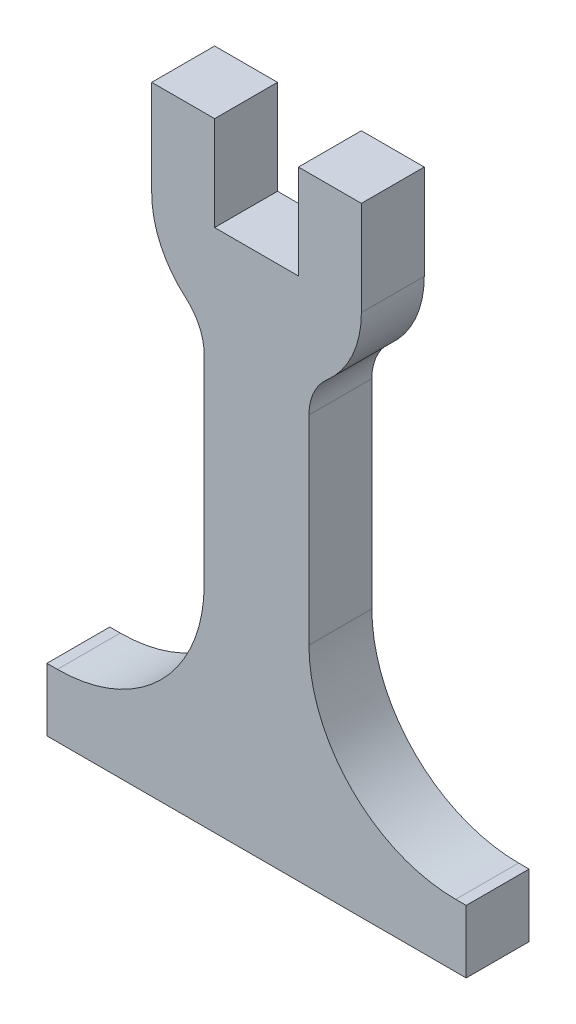
SolidWorks part; units mm, degrees
material "Pinho"
ref_plane "Plano frontal" through (0, 0, 0) normal (0, 0, 1) x (1, 0, 0)
ref_plane "Plano superior" through (0, 0, 0) normal (0, 1, 0) x (1, 0, 0)
ref_plane "Plano direito" through (0, 0, 0) normal (1, 0, 0) x (0, 0, -1)
sketch "Esboço1" plane through (0, 0, 0) normal (0, 0, 1) x (1, 0, 0)
  line L0 (3, 0) -> (7, 0)
  line L2 (0, 0) -> (0, 3)
  line L4 (3, 0) -> (3, 3)
  line L5 (2.5, -6.25) -> (2.5, -5.4903)
  line L7 (7, 0) -> (7, 3)
  line L9 (10, 0) -> (10, 3)
  line L10 (0, -25) -> (10, -25)
  line L11 (7.5, -5.4903) -> (7.5, -6.25)
  line L12 (-5, -25) -> (15, -25)
  line L13 (0, 0) -> (0, -0.0759)
  line L14 (3, 3) -> (3, 4.5)
  line L15 (2.5, -12.5) -> (2.5, -6.25)
  line L16 (7.5, -12.5) -> (7.5, -6.25)
  line L17 (10, 0) -> (10, -0.0154)
  line L18 (10, -3) -> (9.9903, -3)
  line L19 (2.5, -12.5) -> (2.5, -15)
  line L20 (0, -3) -> (0.0097, -3)
  line L21 (-5, -25) -> (-5, -22)
  line L22 (15, -25) -> (15, -22)
  line L23 (7, 4.5) -> (10, 4.5)
  line L24 (10, 4.5) -> (10, 3)
  line L25 (-5, -22) -> (-4.5, -22)
  line L26 (7, 3) -> (7, 4.5)
  line L27 (14.5, -22) -> (15, -22)
  line L28 (7.5, -15) -> (7.5, -12.5)
  line L29 (0, 3) -> (0, 4.5)
  line L30 (0, 4.5) -> (3, 4.5)
  arc A0 (-4.5, -22) -> (2.5, -15) centre (-4.5, -15) ccw
  arc A1 (14.5, -22) -> (7.5, -15) centre (14.5, -15) cw
  arc A2 (2.5, -5.4903) -> (1.6248, -3.5947) centre (0.0097, -5.4903) ccw
  arc A3 (7.5, -5.4903) -> (8.3593, -3.6084) centre (9.9903, -5.4903) cw
  arc A4 (0, -0.0759) -> (1.6248, -3.5947) centre (4.6229, -0.0759) ccw
  arc A5 (8.3593, -3.6084) -> (10, -0.0154) centre (5.2453, -0.0154) ccw
extrude "Ressalto-extrusão1" add sketch "Esboço1" along normal blind 3 contours L0 L7 L26 L23 L24 L9 L17 A5 A3 L11 L16 L28 A1 L27 L22 L12 L21 L25 A0 L19 L15 L5 A2 A4 L13 L2 L29 L30 L14 L4
